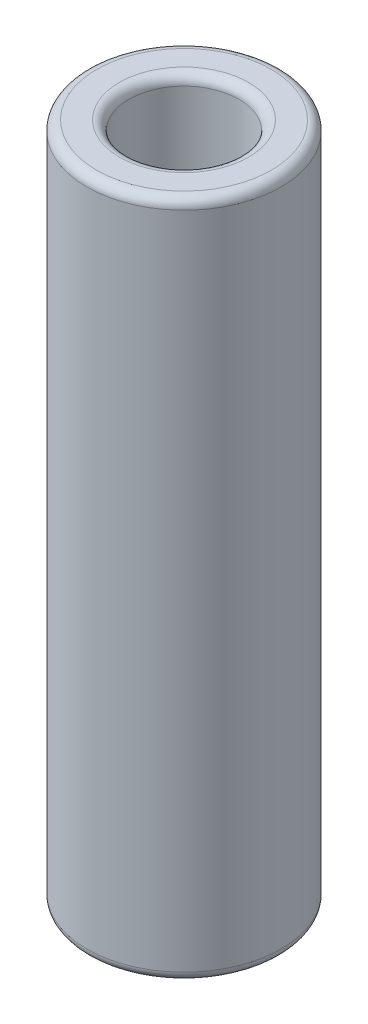
SolidWorks part; units mm, degrees
ref_plane "Front Plane" through (0, 0, 0) normal (0, 0, 1) x (1, 0, 0)
ref_plane "Top Plane" through (0, 0, 0) normal (0, 1, 0) x (1, 0, 0)
ref_plane "Right Plane" through (0, 0, 0) normal (1, 0, 0) x (0, 0, -1)
sketch "Sketch1" plane through (0, 0, 0) normal (0, 1, 0) x (1, 0, 0)
  circle A0 centre (0, 0) radius 3
  circle A1 centre (0, 0) radius 1.7
  dimension "D1" = 6
  dimension "D2" = 3.4
extrude "Boss-Extrude1" add sketch "Sketch1" along normal blind 21
fillet "Fillet1" radius 0.3 4 edges at (0, 0, 1.7) (0, 0, 3) (0, 21, 1.7) (0, 21, 3)
